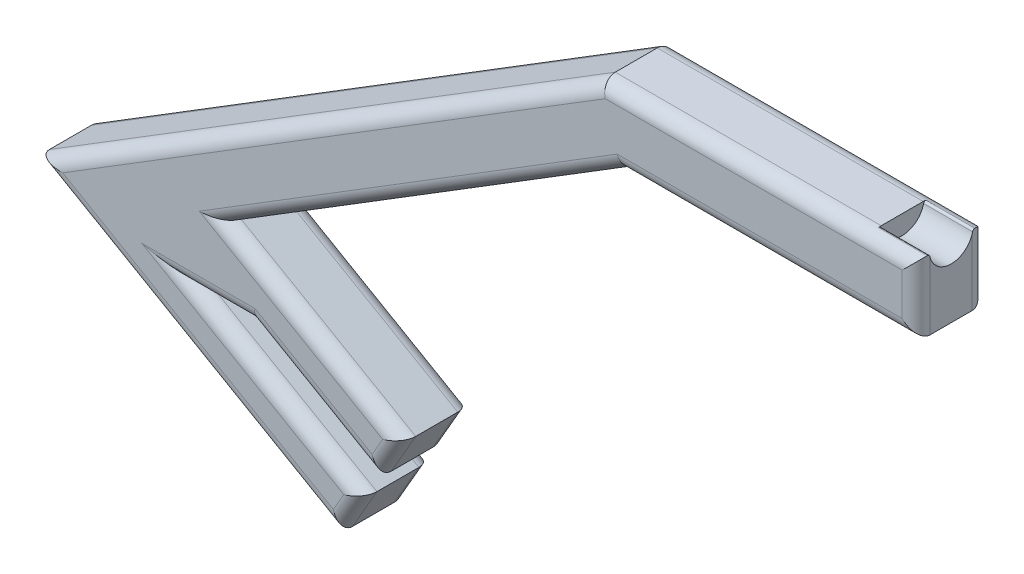
SolidWorks part; units mm, degrees
material "ABS"
ref_plane "Front Plane" through (0, 0, 0) normal (0, 0, 1) x (1, 0, 0)
ref_plane "Top Plane" through (0, 0, 0) normal (0, 1, 0) x (1, 0, 0)
ref_plane "Right Plane" through (0, 0, 0) normal (1, 0, 0) x (0, 0, -1)
sketch "Sketch1" plane through (0, 0, 0) normal (0, 0, 1) x (1, 0, 0)
  line L9 (0, 0) -> (80.8603, 50)
  line L10 (80.8603, 50) -> (125.8603, 50)
  line L11 (125.8603, 50) -> (125.8603, 40)
  line L12 (125.8603, 40) -> (83.7023, 40)
  line L16 (52.3513, -9.3249) -> (48.8513, -15.3871)
  line L17 (48.8513, -15.3871) -> (30.8603, -5)
  line L18 (30.8603, -5) -> (22.6603, -5)
  line L19 (22.6603, -5) -> (46.8013, -18.9378)
  line L20 (46.8013, -18.9378) -> (43.3013, -25)
  line L21 (43.3013, -25) -> (0, 0)
  line L23 (43.3013, -25) -> (96.6202, -25) construction
  line L24 (52.3513, -9.3249) -> (27.3124, 5.1313)
  line L25 (27.3124, 5.1313) -> (83.7023, 40)
  point P8 (72.9418, 124.0428)
  point P14 (23.2089, 5.9373)
  point P16 (18.1389, 5.6933)
  point P17 (89.9048, 52.6117)
  point P18 (9.541, 0.265)
  point P19 (18, 5.635)
  point P20 (15.2341, -3.0219)
  dimension "D1" = 45
  dimension "D2" = 8.2
  dimension "D3" = 7
  dimension "D4" = 50
  dimension "D5" = 30
  dimension "D6" = 10
  dimension "D7" = 10
  dimension "D8" = 95
  dimension "D9" = 45
  dimension "D10" = 5
extrude "Boss-Extrude1" add sketch "Sketch1" along normal mid plane 10
fillet "Fillet1" radius 2 24 edges at (45.0513, -21.9689, -5) (34.7308, -11.9689, -5) (26.7603, -5, -5) (39.8558, -10.1936, -5) (50.6013, -12.356, -5) (39.8318, -2.0968, -5) (55.5073, 22.5656, -5) (104.7813, 40, -5) (125.8603, 45, -5) (103.3603, 50, -5) (40.4301, 25, -5) (21.6506, -12.5, -5) (40.4301, 25, 5) (103.3603, 50, 5) (125.8603, 45, 5) (104.7813, 40, 5) (55.5073, 22.5656, 5) (39.8318, -2.0968, 5) (50.6013, -12.356, 5) (39.8558, -10.1936, 5) (26.7603, -5, 5) (34.7308, -11.9689, 5) (45.0513, -21.9689, 5) (21.6506, -12.5, 5)
sketch "Sketch2" plane through (125.8603, 0, 0) normal (1, 0, 0) x (0, 0, -1)
  line L1 (-3, 50) -> (3, 50) construction
  circle A0 centre (0, 50.4) radius 3.125
  point P2 (0, 0)
  point P6 (0, 50)
  dimension "D1" = 6.25
  dimension "D2" = 0.4
extrude "Cut-Extrude1" cut sketch "Sketch2" against normal blind 7
fillet "Fillet2" radius 0.3 2 edges at (122.359, 49.9975, 3.099) (122.359, 49.9975, -3.099)
